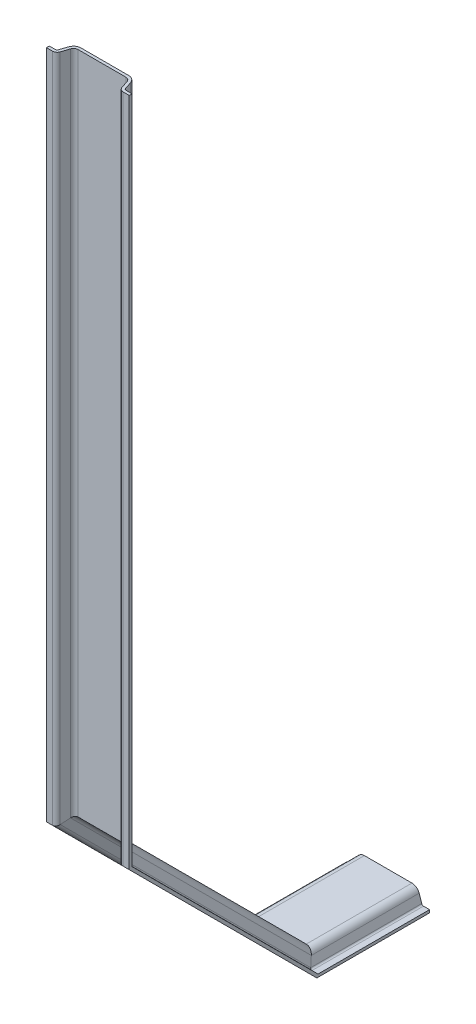
SolidWorks part; units mm, degrees
material "镀铬不锈钢"
ref_plane "前视基准面" through (0, 0, 0) normal (0, 0, 1) x (1, 0, 0)
ref_plane "上视基准面" through (0, 0, 0) normal (0, 1, 0) x (1, 0, 0)
ref_plane "右视基准面" through (0, 0, 0) normal (1, 0, 0) x (0, 0, -1)
sketch "草图1" plane through (0, 0, 0) normal (1, 0, 0) x (0, 0, -1)
  line L0 (-134.2721, 210.3) -> (-211.87, 132.7021)
  line L1 (-211.87, 132.7021) -> (-211.87, -150.705)
  line L2 (-211.87, -150.705) -> (-132.575, -230)
  line L3 (0, 0) -> (0, -268.8719) construction
  line L4 (211.87, -150.705) -> (132.575, -230) construction
  line L5 (211.87, 132.7021) -> (211.87, -150.705) construction
  line L6 (134.2721, 210.3) -> (211.87, 132.7021) construction
  line L7 (-132.575, -230) -> (132.575, -230) construction
  line L8 (-132.575, -230) -> (-84.915, -230)
  line L9 (-84.915, -230) -> (-84.915, -220) construction
  dimension "D1" = 265.15
  dimension "D2" = 45
  dimension "D3" = 45
  dimension "D4" = 440.3
  dimension "D5" = 112.14
  dimension "D6" = 109.74
  dimension "D7" = 230
  dimension "D8" = 47.66
ref_plane "基准面1" through (0, 132.7021, 211.87) normal (0, 1, 0) x (1, 0, 0)
sketch "草图2" plane through (0, 132.7021, 211.87) normal (0, 1, 0) x (1, 0, 0)
  line L0 (17.5, 0) -> (14.9415, 0)
  line L1 (13.0442, 1.3675) -> (11.9558, 4.6325)
  line L2 (10.0585, 6) -> (-10.0585, 6)
  line L3 (17.5, 1.2) -> (14.9415, 1.2)
  line L4 (0, 6) -> (0, 1.9514) construction
  line L5 (-13.0442, 1.3675) -> (-11.9558, 4.6325)
  line L6 (-17.5, 0) -> (-14.9415, 0)
  line L7 (14.1826, 1.747) -> (13.0943, 5.0119)
  line L8 (10.0585, 7.2) -> (-10.0585, 7.2)
  line L9 (-14.1826, 1.747) -> (-13.0943, 5.0119)
  line L10 (-17.5, 1.2) -> (-14.9415, 1.2)
  line L11 (-17.5, 1.2) -> (-17.5, 0)
  line L12 (17.5, 1.2) -> (17.5, 0)
  line L14 (0, 0) -> (0, 79.295) construction
  arc A0 (11.9558, 4.6325) -> (10.0585, 6) centre (10.0585, 4) ccw
  arc A1 (14.9415, 0) -> (13.0442, 1.3675) centre (14.9415, 2) cw
  arc A2 (-14.9415, 0) -> (-13.0442, 1.3675) centre (-14.9415, 2) ccw
  arc A3 (-11.9558, 4.6325) -> (-10.0585, 6) centre (-10.0585, 4) cw
  arc A4 (14.9415, 1.2) -> (14.1826, 1.747) centre (14.9415, 2) cw
  arc A5 (13.0943, 5.0119) -> (10.0585, 7.2) centre (10.0585, 4) ccw
  arc A6 (-13.0943, 5.0119) -> (-10.0585, 7.2) centre (-10.0585, 4) cw
  arc A7 (-14.9415, 1.2) -> (-14.1826, 1.747) centre (-14.9415, 2) ccw
  point P10 (11.5, 6)
  point P13 (13.5, 0)
  point P21 (-13.5, 0)
  point P22 (-11.5, 6)
  dimension "D5" = 2
  dimension "D1" = 35
  dimension "D2" = 6
  dimension "D3" = 11.5
  dimension "D4" = 4
  dimension "D6" = 1.2
sweep "扫描1" add profiles "草图2" path "草图1"
